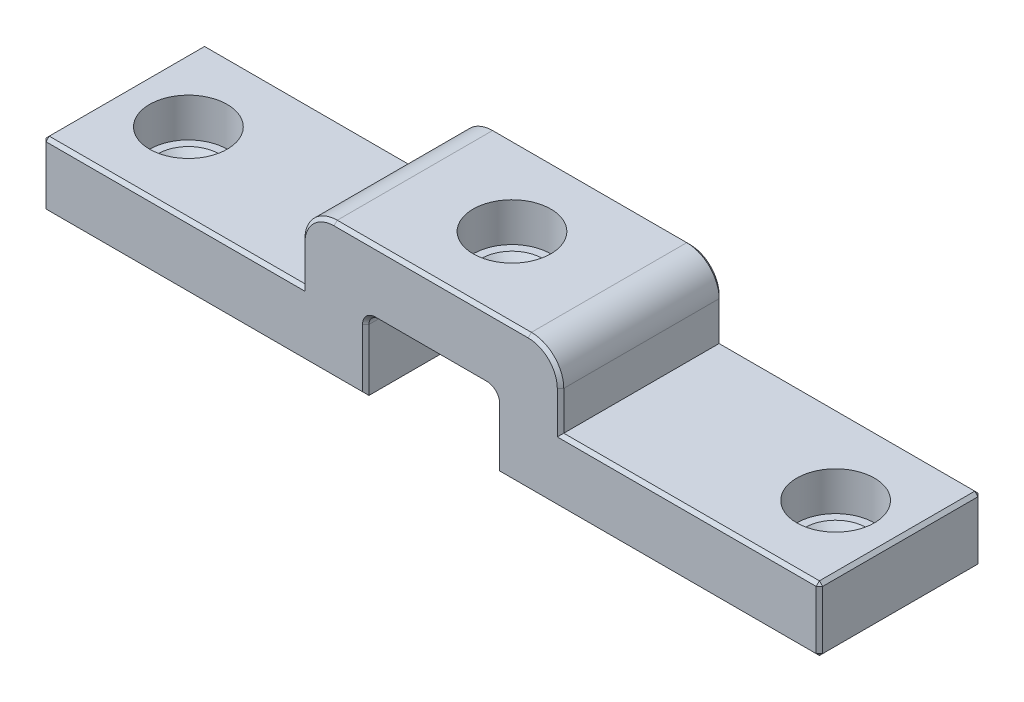
SolidWorks part; units mm, degrees
ref_plane "Front Plane" through (0, 0, 0) normal (0, 0, 1) x (1, 0, 0)
ref_plane "Top Plane" through (0, 0, 0) normal (0, 1, 0) x (1, 0, 0)
ref_plane "Right Plane" through (0, 0, 0) normal (1, 0, 0) x (0, 0, -1)
sketch "Sketch1" plane through (0, 0, 0) normal (0, 1, 0) x (1, 0, 0)
  line L1 (60, -12.5) -> (-60, -12.5)
  line L2 (60, -12.5) -> (60, 12.5)
  line L3 (60, 12.5) -> (-60, 12.5)
  line L4 (-60, -12.5) -> (-60, 12.5)
  line L5 (60, -12.5) -> (-60, 12.5) construction
  line L6 (60, 12.5) -> (-60, -12.5) construction
  point P0 (0, 0)
  dimension "D1" = 120
  dimension "D2" = 25
extrude "Boss-Extrude1" add sketch "Sketch1" along normal blind 10
sketch "Sketch2" plane through (0, 10, 0) normal (0, 1, 0) x (1, 0, 0)
  line L0 (60, 12.5) -> (-60, 12.5) construction
  line L1 (20, -12.5) -> (-20, -12.5)
  line L2 (20, -12.5) -> (20, 12.5)
  line L3 (20, 12.5) -> (-20, 12.5)
  line L4 (-20, -12.5) -> (-20, 12.5)
  line L5 (20, -12.5) -> (-20, 12.5) construction
  line L6 (20, 12.5) -> (-20, -12.5) construction
  point P0 (0, 0)
  dimension "D1" = 40
extrude "Boss-Extrude2" add sketch "Sketch2" along normal blind 11
sketch "Sketch3" plane through (0, 0, 0) normal (0, 1, 0) x (1, 0, 0)
  line L0 (20, 12.5) -> (-20, 12.5) construction
  line L1 (10.1, -12.5) -> (-10.1, -12.5)
  line L2 (10.1, -12.5) -> (10.1, 12.5)
  line L3 (10.1, 12.5) -> (-10.1, 12.5)
  line L4 (-10.1, -12.5) -> (-10.1, 12.5)
  line L5 (10.1, -12.5) -> (-10.1, 12.5) construction
  line L6 (10.1, 12.5) -> (-10.1, -12.5) construction
  point P0 (0, 0)
  dimension "D1" = 20.2
extrude "Cut-Extrude1" cut sketch "Sketch3" along normal blind 11
sketch "Sketch4" plane through (0, 11, 0) normal (0, -1, 0) x (1, 0, 0)
  line L0 (-50, 0) -> (0, 0) construction
  line L1 (0, 0) -> (50, 0) construction
  circle A0 centre (0, 0) radius 2.75
  circle A1 centre (-50, 0) radius 2.75
  circle A2 centre (50, 0) radius 2.75
  dimension "D1" = 5.5
  dimension "D2" = 50
extrude "Cut-Extrude2" cut sketch "Sketch4" against normal through all both and the other way through all
fillet "Fillet1" radius 5 2 edges at (-20, 21, 0) (20, 21, 0)
fillet "Fillet2" radius 1.5 2 edges at (10.1, 11, 0) (-10.1, 11, 0)
chamfer "Chamfer1" distance 0.5 angle 45 36 edges at (60, 10, 0) (60, 0, 0) (-60, 10, 0) (-35.05, 0, 12.5) (-10.1, 4.75, 12.5) (0, 11, 12.5) (10.1, 4.75, 12.5) (35.05, 0, 12.5) (60, 5, 12.5) (40, 10, 12.5) (20, 13, 12.5) (0, 21, 12.5) (-20, 13, 12.5) (-40, 10, 12.5) (-60, 5, 12.5) (-60, 0, 0) (0, 11, -12.5) (10.1, 4.75, -12.5) (35.05, 0, -12.5) (60, 5, -12.5) (40, 10, -12.5) (20, 13, -12.5) (0, 21, -12.5) (-20, 13, -12.5) (-40, 10, -12.5) (-60, 5, -12.5) (-35.05, 0, -12.5) (-10.1, 4.75, -12.5) (18.5355, 19.5355, 12.5) (9.6607, 10.5607, 12.5) (-9.6607, 10.5607, 12.5) (-18.5355, 19.5355, 12.5) (-9.6607, 10.5607, -12.5) (9.6607, 10.5607, -12.5) (18.5355, 19.5355, -12.5) (-18.5355, 19.5355, -12.5)
sketch "Sketch5" plane through (0, 10, 0) normal (0, 1, 0) x (1, 0, 0)
  circle A0 centre (-50, 0) radius 6
  circle A2 centre (50, 0) radius 6
  dimension "D1" = 12
extrude "Cut-Extrude3" cut sketch "Sketch5" against normal blind 6
chamfer "Chamfer2" distance 2 angle 45 2 edges at (-50, 4, 2.75) (50, 4, 2.75)
sketch "Sketch6" plane through (0, 21, 0) normal (0, 1, 0) x (1, 0, 0)
  circle A0 centre (0, 0) radius 6
  dimension "D1" = 12
extrude "Cut-Extrude4" cut sketch "Sketch6" against normal blind 6
chamfer "Chamfer3" distance 2 angle 45 1 edges at (0, 15, 2.75)
